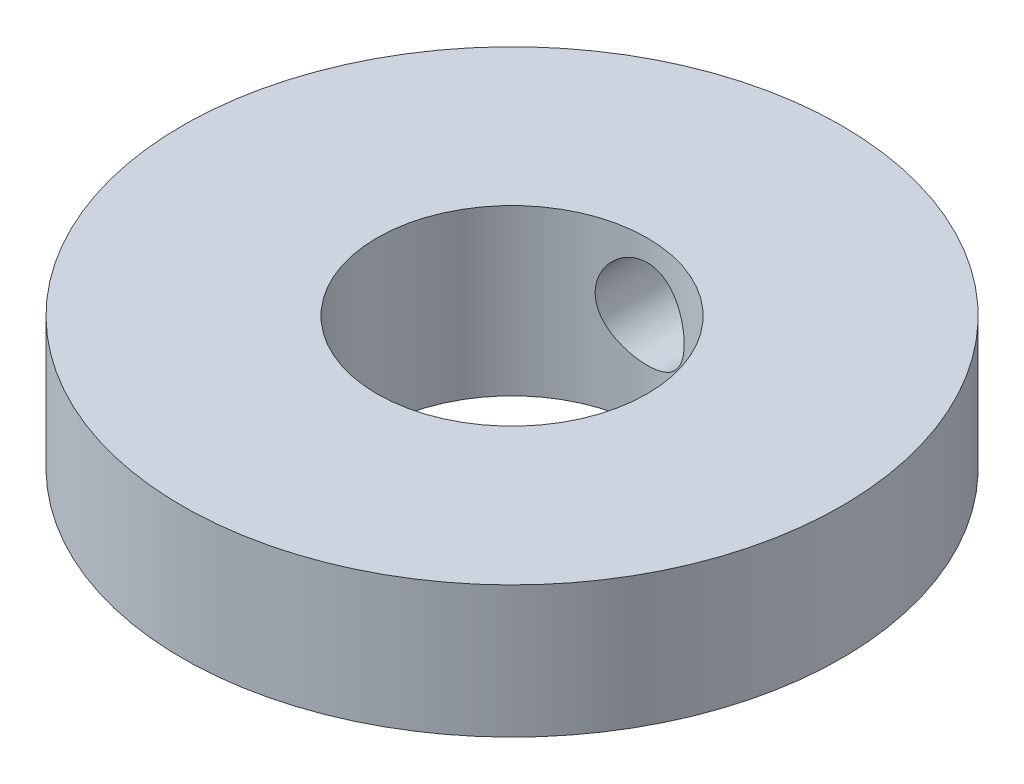
SolidWorks part; units mm, degrees
ref_plane "Front Plane" through (0, 0, 0) normal (0, 0, 1) x (1, 0, 0)
ref_plane "Top Plane" through (0, 0, 0) normal (0, 1, 0) x (1, 0, 0)
ref_plane "Right Plane" through (0, 0, 0) normal (1, 0, 0) x (0, 0, -1)
sketch "Sketch1" plane through (0, 0, 0) normal (1, 0, 0) x (0, 0, -1)
  line L0 (-4.1, 0) -> (-5, 0)
  line L2 (-6, 1) -> (-10, 1)
  line L3 (-10, 1) -> (-10, 5)
  line L4 (-10, 5) -> (-4.1, 5)
  line L5 (-4.1, 5) -> (-4.1, 0)
  line L6 (0, 0) -> (0, 7.6289) construction
  line L7 (-5, 0) -> (-6, 1)
  dimension "D1" = 135
  dimension "D2" = 8.2
  dimension "D3" = 5
  dimension "D4" = 1
  dimension "D5" = 10
  dimension "D6" = 20
revolve "Revolve1" add sketch "Sketch1" angle 360 about L6
ref_plane "Plane1" through (0, 0, -10) normal (0, 0, -1) x (-1, 0, 0)
sketch "Sketch2" plane through (0, 0, -10) normal (0, 0, -1) x (-1, 0, 0)
  line L0 (0, 1) -> (0, 5) construction
  line L1 (-6, 1) -> (6, 1) construction
  line L2 (10, 5) -> (-10, 5) construction
  point P0 (0, 3)
  point P9 (0, 3)
hole_wizard "Ø2.7 (2.7) Diameter Hole1" positions "Sketch2" profile "Sketch3" hole size "Ø2.7" standard "ANSI Metric"
sketch "Sketch3" plane through (0, 3, -10) normal (1, 0, 0) x (0, 1, 0)
  line L0 (0, 0) -> (0, 5.9)
  line L1 (0, 5.9) -> (1.35, 5.9)
  line L2 (1.35, 5.9) -> (1.35, 0)
  line L5 (1.35, 0) -> (0, 0)
  line L11 (0, -6.35) -> (0, 107.95) construction
  dimension "Thru Hole Dia." = 2.7
  dimension "Thru Hole Depth" = 5.9
